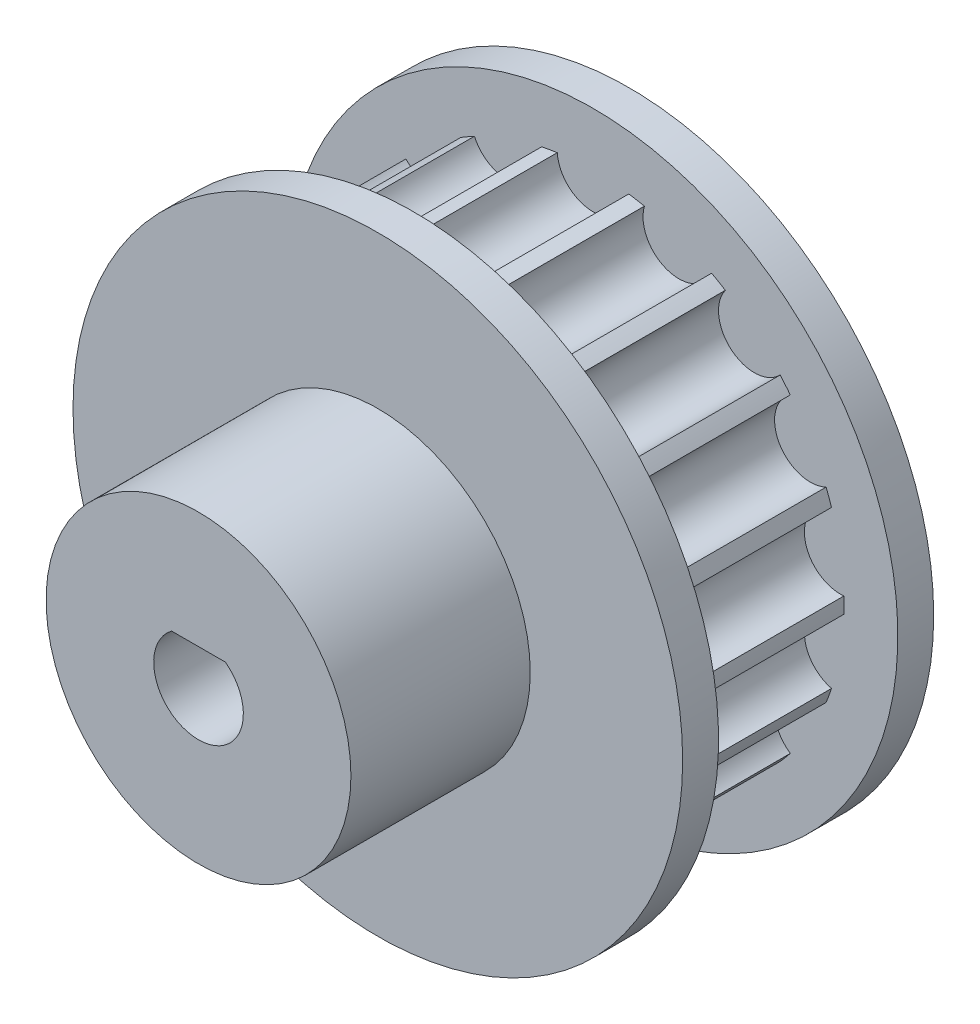
SolidWorks part; units mm, degrees
ref_plane "前视基准面" through (0, 0, 0) normal (0, 0, 1) x (1, 0, 0)
ref_plane "上视基准面" through (0, 0, 0) normal (0, 1, 0) x (1, 0, 0)
ref_plane "右视基准面" through (0, 0, 0) normal (1, 0, 0) x (0, 0, -1)
sketch "Sketch1" plane through (0, 0, 0) normal (0, 0, 1) x (1, 0, 0)
  circle A0 centre (0, 0) radius 17
  dimension "D1" = 34
extrude "Boss-Extrude1" add sketch "Sketch1" along normal blind 14
sketch "Sketch3" plane through (0, 0, 14) normal (0, 0, 1) x (1, 0, 0)
  circle A0 centre (0, 0) radius 2.5
  dimension "D1" = 5
extrude "Cut-Extrude2" cut sketch "Sketch3" against normal up to next
sketch "Sketch5" plane through (0, 0, 14) normal (0, 0, 1) x (1, 0, 0)
  circle A0 centre (0, 0) radius 2.5
  circle A1 centre (0, 0) radius 8.5
  dimension "D1" = 17
extrude "Boss-Extrude2" add sketch "Sketch5" along normal blind 10
sketch "Sketch6" plane through (0, 0, 24) normal (0, 0, 1) x (1, 0, 0)
  line L0 (-1.5691, 2) -> (1.4281, 2) construction
  line L1 (1.5, 2) -> (-1.5, 2)
  arc A0 (1.5, 2) -> (-1.5, 2) centre (0, 0) ccw
  dimension "D1" = 2
extrude "Boss-Extrude3" add sketch "Sketch6" against normal up to surface (24 mm away) up to face at (2.5, 0, 0)
ref_plane "Plane1" through (0, 0, 7) normal (0, 0, -1) x (-1, 0, 0)
sketch "Sketch7" plane through (0, 0, 7) normal (0, 0, -1) x (-1, 0, 0)
  circle A0 centre (0, 0) radius 17
  circle A1 centre (0, 0) radius 14
extrude "Cut-Extrude5" cut sketch "Sketch7" against normal mid plane 10
sketch "Sketch8" plane through (0, 0, 7) normal (0, 0, -1) x (-1, 0, 0)
  circle A0 centre (0, 0) radius 14 construction
  circle A1 centre (0, 14) radius 2
  circle A2 centre (4.7883, 13.1557) radius 2
  circle A3 centre (8.999, 10.7246) radius 2
  circle A4 centre (12.1244, 7) radius 2
  circle A5 centre (13.7873, 2.4311) radius 2
  circle A6 centre (13.7873, -2.4311) radius 2
  circle A7 centre (12.1244, -7) radius 2
  circle A8 centre (8.999, -10.7246) radius 2
  circle A9 centre (4.7883, -13.1557) radius 2
  circle A10 centre (0, -14) radius 2
  circle A11 centre (-4.7883, -13.1557) radius 2
  circle A12 centre (-8.999, -10.7246) radius 2
  circle A13 centre (-12.1244, -7) radius 2
  circle A14 centre (-13.7873, -2.4311) radius 2
  circle A15 centre (-13.7873, 2.4311) radius 2
  circle A16 centre (-12.1244, 7) radius 2
  circle A17 centre (-8.999, 10.7246) radius 2
  circle A18 centre (-4.7883, 13.1557) radius 2
  dimension "D1" = 18
  dimension "D2" = 4
extrude "Cut-Extrude6" cut sketch "Sketch8" against normal mid plane 10
